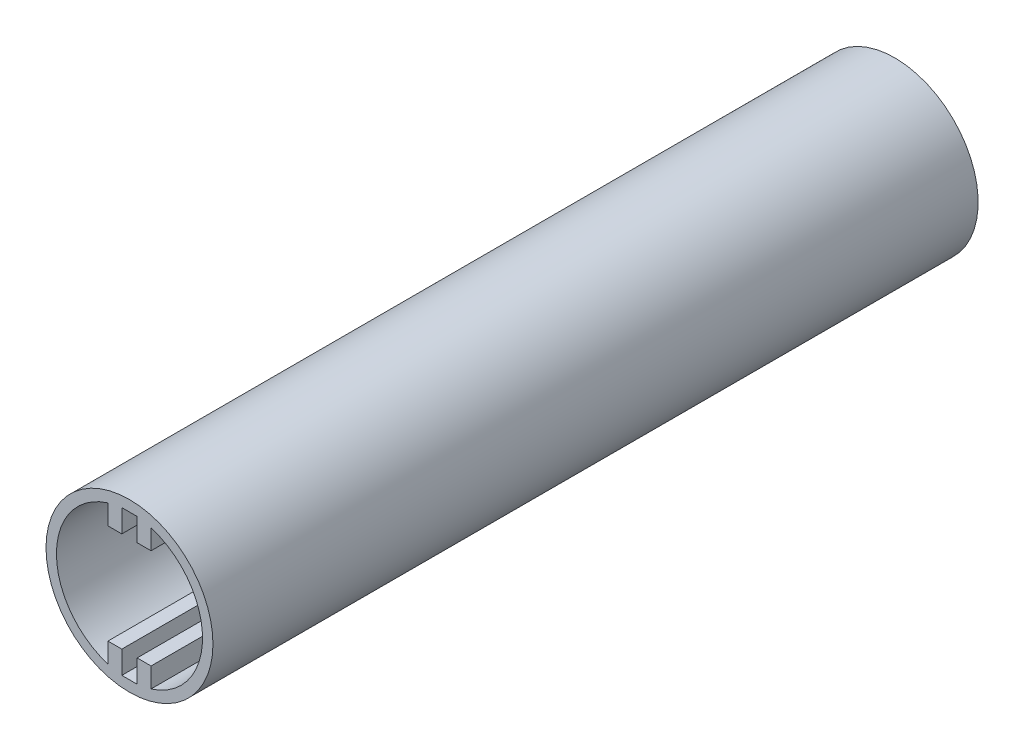
SolidWorks part; units mm, degrees
ref_plane "Front Plane" through (0, 0, 0) normal (0, 0, 1) x (1, 0, 0)
ref_plane "Top Plane" through (0, 0, 0) normal (0, 1, 0) x (1, 0, 0)
ref_plane "Right Plane" through (0, 0, 0) normal (1, 0, 0) x (0, 0, -1)
sketch "Sketch1" plane through (0, 0, 0) normal (0, 0, 1) x (1, 0, 0)
  line L0 (0, 0) -> (0, 7.8601) construction
  line L5 (1.55, -5.016) -> (1.55, -3.5852)
  line L6 (1.55, -3.5852) -> (0.55, -3.5852)
  line L7 (-6.5394, 0) -> (7.4478, 0) construction
  line L8 (-1.55, 5.016) -> (-1.55, 3.5852)
  line L9 (-1.55, 3.5852) -> (-0.55, 3.5852)
  line L10 (1.55, 3.5852) -> (0.55, 3.5852)
  line L11 (1.55, 5.016) -> (1.55, 3.5852)
  line L12 (-0.55, 3.5852) -> (-0.55, 5.2211)
  line L13 (0.55, 3.5852) -> (0.55, 5.2211)
  line L14 (0.55, -3.5852) -> (0.55, -5.2211)
  line L15 (-0.55, -3.5852) -> (-0.55, -5.2211)
  line L16 (-1.55, -3.5852) -> (-0.55, -3.5852)
  line L17 (-1.55, -5.016) -> (-1.55, -3.5852)
  line L18 (-0.55, -5.2211) -> (0.55, -5.2211)
  line L19 (-0.55, 5.2211) -> (0.55, 5.2211)
  arc A0 (-1.55, 5.016) -> (-1.55, -5.016) centre (0, 0) ccw
  circle A1 centre (0, 0) radius 6
  arc A4 (1.55, -5.016) -> (1.55, 5.016) centre (0, 0) ccw
  dimension "D1" = 10.5
  dimension "D2" = 12
  dimension "D3" = 1.1
  dimension "D4" = 1
  dimension "D5" = 1.1
  dimension "D6" = 1.4308
extrude "Boss-Extrude1" add sketch "Sketch1" along normal mid plane 35
sketch "Sketch2" plane through (0, 0, -17.5) normal (0, 0, -1) x (-1, 0, 0)
  circle A0 centre (0, 0) radius 6
  circle A1 centre (0, 0) radius 5.25
extrude "Boss-Extrude2" add sketch "Sketch2" along normal blind 20
